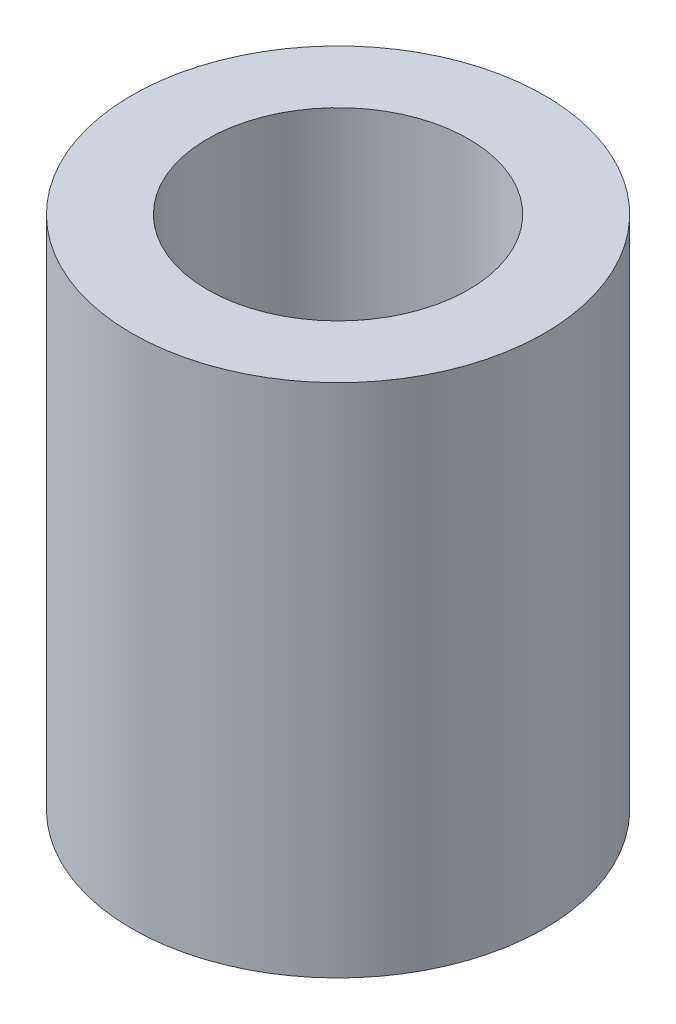
SolidWorks part; units mm, degrees
ref_plane "Front Plane" through (0, 0, 0) normal (0, 0, 1) x (1, 0, 0)
ref_plane "Top Plane" through (0, 0, 0) normal (0, 1, 0) x (1, 0, 0)
ref_plane "Right Plane" through (0, 0, 0) normal (1, 0, 0) x (0, 0, -1)
sketch "Sketch1" plane through (0, 0, 0) normal (0, 1, 0) x (1, 0, 0)
  circle A0 centre (0, 0) radius 3
  circle A1 centre (0, 0) radius 1.9
  dimension "D1" = 6
  dimension "D2" = 3.8
extrude "Boss-Extrude1" add sketch "Sketch1" along normal blind 7.5
